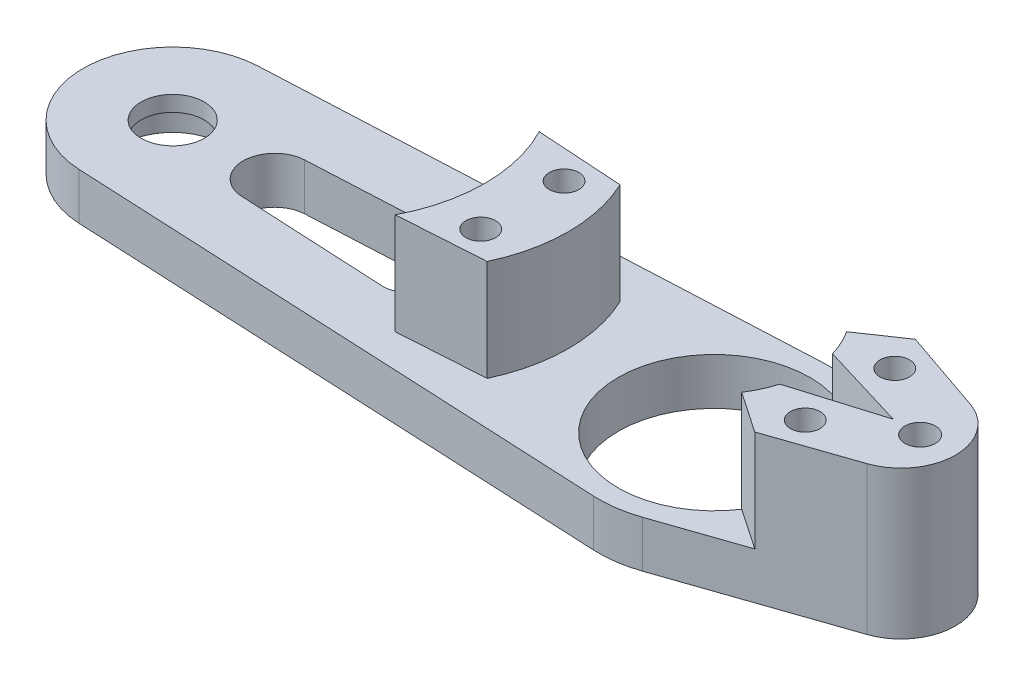
SolidWorks part; units mm, degrees
ref_plane "Front Plane" through (0, 0, 0) normal (0, 0, 1) x (1, 0, 0)
ref_plane "Top Plane" through (0, 0, 0) normal (0, 1, 0) x (1, 0, 0)
ref_plane "Right Plane" through (0, 0, 0) normal (1, 0, 0) x (0, 0, -1)
sketch "Sketch1" plane through (0, 0, 0) normal (0, 1, 0) x (1, 0, 0)
  line L16 (-0.546, 11.487) -> (68.7973, 14.7833)
  line L19 (-0.546, -11.487) -> (68.7973, -14.7833)
  line L36 (69.5, 0) -> (93.5, 0) construction
  line L37 (0, 0) -> (69.5, 0) construction
  line L38 (44.9, 5.35) -> (44.9, -5.35) construction
  line L46 (12.8982, 4.045) -> (31.9754, 4.9969)
  line L47 (34.6, 2.5) -> (34.6, -2.5)
  line L48 (31.9754, -4.9969) -> (12.8982, -4.045)
  line L49 (1.704, 18.572) -> (70.6238, 12.2486) construction
  line L50 (0, -18.65) -> (70.6103, -12.2498) construction
  line L51 (74.31, 13.9966) -> (95.775, 6.62)
  line L52 (74.31, -13.9966) -> (95.775, -6.62)
  line L53 (86.96, -5.75) -> (86.96, 5.75) construction
  line L54 (93.5, 0) -> (95.96, 0) construction
  arc A1 (-0.546, 11.487) -> (-0.546, -11.487) centre (0, 0) ccw
  circle A2 centre (44.9, -5.35) radius 1.9
  circle A5 centre (0, 0) radius 4.05
  circle A6 centre (44.9, 5.35) radius 1.9
  arc A7 (34.6, 2.5) -> (31.9754, 4.9969) centre (32.1, 2.5) ccw
  arc A8 (31.9754, -4.9969) -> (34.6, -2.5) centre (32.1, -2.5) ccw
  arc A9 (12.8982, 4.045) -> (12.8982, -4.045) centre (13.1, 0) ccw
  circle A10 centre (0, 0) radius 18.65 construction
  circle A12 centre (69.5, 0) radius 12.3
  circle A13 centre (69.5, 0) radius 14.8
  arc A14 (95.775, -6.62) -> (95.775, 6.62) centre (93.5, 0) ccw
  circle A15 centre (86.96, 5.75) radius 1.9
  circle A16 centre (86.96, -5.75) radius 1.9
  circle A17 centre (95.96, 0) radius 1.95
  point P8 (34.75, 0)
  point P10 (44.9, 0)
  point P13 (34.6, 0)
  point P42 (86.96, 0)
  dimension "D1" = 23
  dimension "D2" = 7
  dimension "D3" = 3.8
  dimension "D4" = 8.1
  dimension "D6" = 37.3
  dimension "D7" = 24.6
  dimension "D14" = 2.5
  dimension "D17" = 2.5
  dimension "D5" = 3.8
  dimension "D16" = 3.9
  dimension "D8" = 69.5
  dimension "D9" = 10.7
  dimension "D10" = 44.9
  dimension "D11" = 5
  dimension "D12" = 13.1
  dimension "D13" = 19
  dimension "D15" = 11.5
  dimension "D18" = 2.46
  dimension "D19" = 17.46
  dimension "D20" = 24
extrude "Boss-Extrude1" add sketch "Sketch1" along normal blind 6 contours A13 L16 A1 L19 A9 L46 A7 L47 A8 L48 A6 A5 A2 | A13 | L52 A14 L51 A13 A17 A16 A15
sketch "Sketch2" plane through (0, 0, 0) normal (0, 1, 0) x (1, 0, 0)
  circle A0 centre (0, 0) radius 6.55
  dimension "D1" = 13.1
extrude "Cut-Extrude1" cut sketch "Sketch2" along normal offset from surface (4 mm away) 2 up to face at (58.8148, 6, 0)
sketch "Sketch3" plane through (0, 6, 0) normal (0, 1, 0) x (1, 0, 0)
  line L1 (48.9, 8.53) -> (48.9, -8.53) construction
  line L2 (44.9, 5.35) -> (44.9, -5.35) construction
  line L5 (37.8102, 9.2435) -> (48.9, 8.53)
  line L6 (37.8102, 0) -> (54.6792, 0) construction
  line L7 (37.8102, -9.2435) -> (48.9, -8.53)
  line L11 (37.8102, -9.2435) -> (37.8102, 9.2435) construction
  circle A0 centre (44.9, -5.35) radius 1.9
  circle A1 centre (44.9, 5.35) radius 1.9
  arc A2 (48.9, -8.53) -> (48.9, 8.53) centre (30.8102, 0) ccw
  arc A3 (37.8102, -9.2435) -> (37.8102, 9.2435) centre (20.0745, 0) ccw
  point P9 (50.8102, 0)
  point P10 (44.9, 0)
  point P19 (44.9, 5.35)
  dimension "D1" = 3.8
  dimension "D6" = 20
  dimension "D2" = 17.06
  dimension "D3" = 10.7
  dimension "D4" = 4
  dimension "D5" = 93.681
  dimension "D7" = 13
extrude "Boss-Extrude3" add sketch "Sketch3" along normal blind 13
sketch "Sketch4" plane through (0, 6, 0) normal (0, 1, 0) x (1, 0, 0)
  line L0 (85.0425, 10.3083) -> (79.7909, 6.737)
  line L1 (74.31, 13.9966) -> (95.775, 6.62) construction
  line L2 (85.0425, -10.3083) -> (79.7909, -6.737)
  line L3 (74.31, -13.9966) -> (95.775, -6.62) construction
  line L4 (85.0425, 10.3083) -> (95.775, 6.62)
  line L5 (85.0425, -10.3083) -> (95.775, -6.62)
  line L7 (81.3245, -3.3869) -> (92.5, 0)
  line L8 (92.5, 0) -> (81.3245, 3.3869)
  circle A0 centre (86.96, 5.75) radius 1.9
  circle A1 centre (86.96, 5.75) radius 1.9 construction
  circle A2 centre (86.96, -5.75) radius 1.9
  circle A3 centre (86.96, -5.75) radius 1.9 construction
  circle A4 centre (95.96, 0) radius 1.95
  circle A5 centre (95.96, 0) radius 1.95 construction
  arc A6 (95.775, -6.62) -> (95.775, 6.62) centre (93.5, 0) ccw
  arc A7 (79.7909, -6.737) -> (81.3245, -3.3869) centre (69.5, 0) ccw
  circle A9 centre (69.5, 0) radius 12.3 construction
  arc A12 (81.3245, 3.3869) -> (79.7909, 6.737) centre (69.5, 0) ccw
  dimension "D1" = 1
extrude "Boss-Extrude4" add sketch "Sketch4" along normal up to surface (13 mm away) up to face at (44.9, 19, 7.25)
